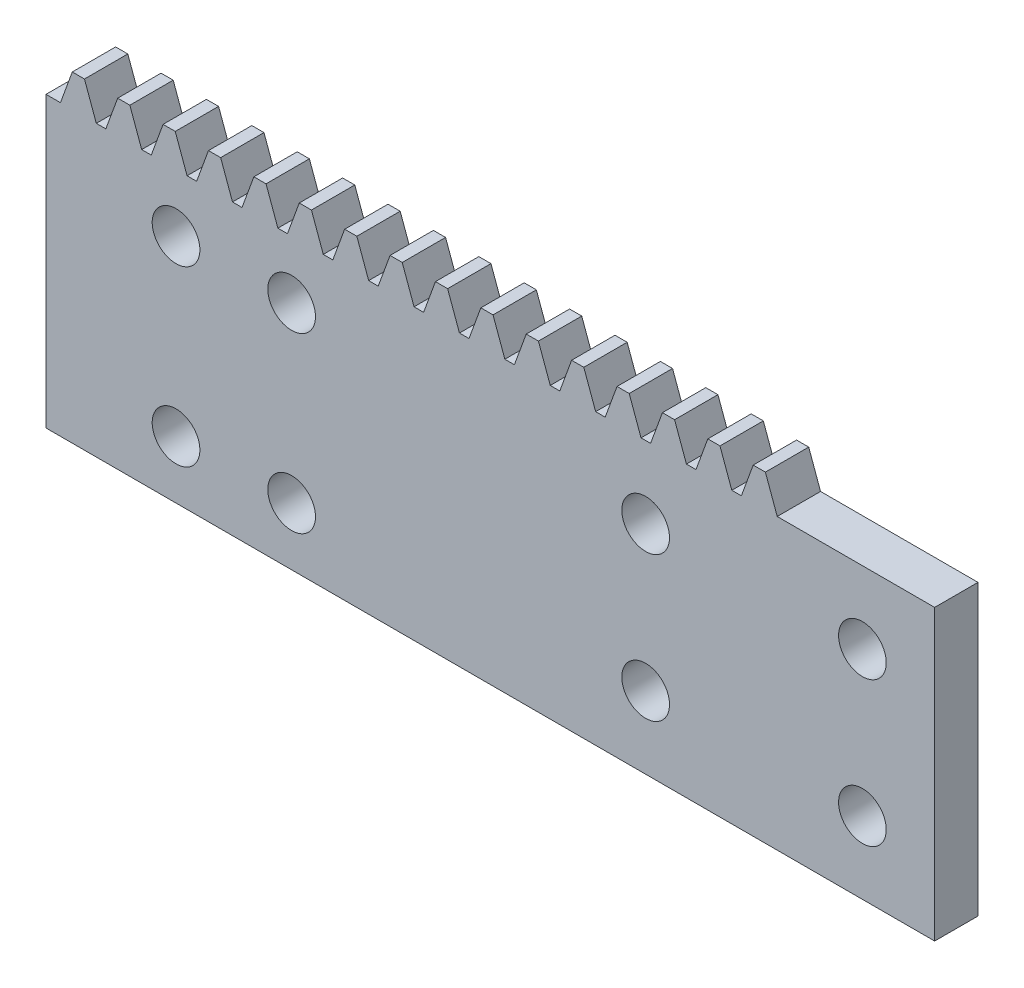
SolidWorks part; units mm, degrees
ref_plane "前基準面" through (0, 0, 0) normal (0, 0, 1) x (1, 0, 0)
ref_plane "上基準面" through (0, 0, 0) normal (0, 1, 0) x (1, 0, 0)
ref_plane "右基準面" through (0, 0, 0) normal (1, 0, 0) x (0, 0, -1)
sketch "草圖1" plane through (0, 0, 0) normal (0, 0, 1) x (1, 0, 0)
  line L1 (-30.75, -10) -> (30.75, -10)
  line L2 (-30.75, -10) -> (-30.75, 10)
  line L3 (-30.75, 10) -> (30.75, 10)
  line L4 (30.75, -10) -> (30.75, 10)
  line L5 (-30.75, -10) -> (30.75, 10) construction
  line L6 (-30.75, 10) -> (30.75, -10) construction
  point P0 (0, 0)
  dimension "D1" = 61.5
  dimension "D2" = 20
extrude "填料-伸長1" add sketch "草圖1" along normal blind 3
sketch "草圖2" plane through (0, 0, 3) normal (0, 0, 1) x (1, 0, 0)
  line L0 (-29.75, 10) -> (-28.9311, 12.25)
  line L1 (30.75, 10) -> (-30.75, 10) construction
  line L2 (-28.9311, 12.25) -> (-28.0882, 12.25)
  line L3 (-28.0882, 12.25) -> (-27.2693, 10)
  line L4 (-29.75, 10) -> (-27.2693, 10)
  line L5 (-29.295, 11.25) -> (-27.7242, 11.25) construction
  dimension "D1" = 2.25
  dimension "D2" = 40
  dimension "D3" = 1
  dimension "D4" = 1
  dimension "D5" = 1.5708
extrude "填料-伸長2" add sketch "草圖2" against normal up to surface (3 mm away) up to face at (0, 0, 0)
pattern_linear "直線複製排列1" count 16 spacing 3.1416 along (1, 0, 0) of "填料-伸長2"
sketch "草圖3" plane through (0, 0, 3) normal (0, 0, 1) x (1, 0, 0)
  line L0 (-30.75, 10) -> (-30.75, -10) construction
  line L5 (-21.75, 6) -> (-13.75, 6) construction
  line L6 (-21.75, 6) -> (-21.75, -6) construction
  line L7 (-21.75, -6) -> (-13.75, -6) construction
  line L8 (-13.75, 6) -> (-13.75, -6) construction
  circle A0 centre (-21.75, 6) radius 1.65
  circle A1 centre (-13.75, 6) radius 1.65
  circle A2 centre (-21.75, -6) radius 1.65
  circle A3 centre (-13.75, -6) radius 1.65
  point P10 (-13.75, 0)
  dimension "D2" = 3.3
  dimension "D3" = 3.3
  dimension "D4" = 3.3
  dimension "D5" = 3.3
  dimension "D1" = 8
  dimension "D6" = 9
  dimension "D7" = 12
extrude "除料-伸長1" cut sketch "草圖3" against normal up to next
sketch "草圖4" plane through (0, 0, 3) normal (0, 0, 1) x (1, 0, 0)
  line L0 (30.75, -10) -> (30.75, 10) construction
  line L1 (10.75, 5) -> (25.75, 5) construction
  line L2 (10.75, 5) -> (10.75, -5) construction
  line L3 (10.75, -5) -> (25.75, -5) construction
  line L4 (25.75, 5) -> (25.75, -5) construction
  circle A0 centre (25.75, 5) radius 1.65
  circle A1 centre (10.75, 5) radius 1.65
  circle A2 centre (25.75, -5) radius 1.65
  circle A3 centre (10.75, -5) radius 1.65
  point P8 (11.1075, -4.8211)
  point P11 (30.75, 0)
  point P12 (25.75, 0)
  dimension "D3" = 3.3
  dimension "D4" = 3.3
  dimension "D5" = 3.3
  dimension "D6" = 3.3
  dimension "D1" = 15
  dimension "D2" = 10
  dimension "D7" = 5
extrude "除料-伸長2" cut sketch "草圖4" against normal up to next
